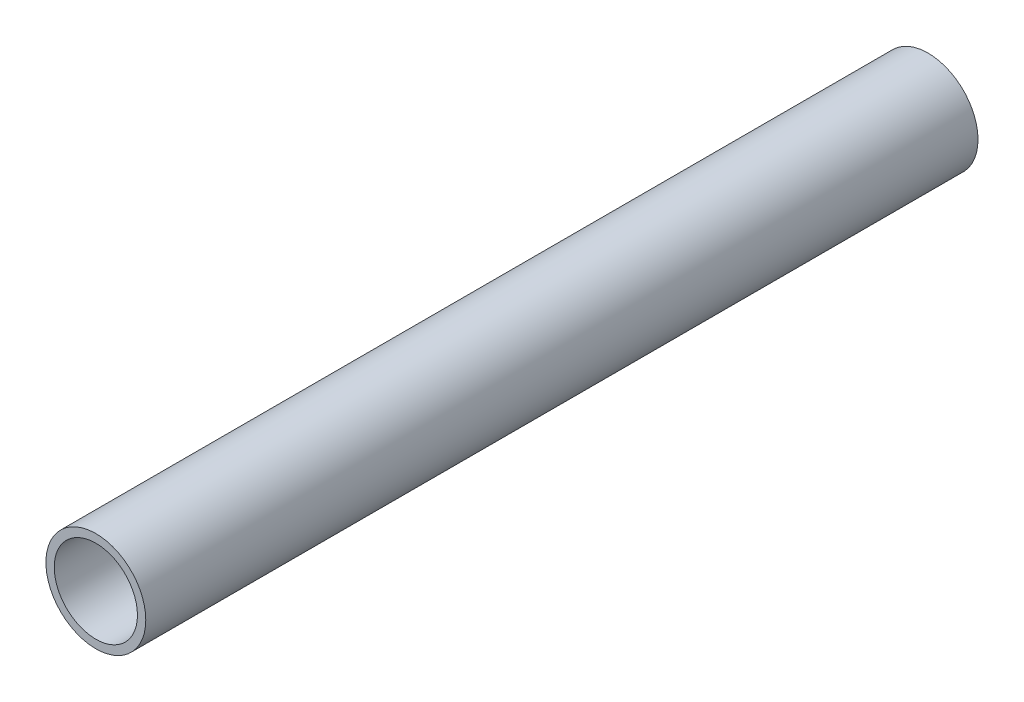
SolidWorks part; units mm, degrees
material "Thornel Mat VMA"
ref_plane "前视基准面" through (0, 0, 0) normal (0, 0, 1) x (1, 0, 0)
ref_plane "上视基准面" through (0, 0, 0) normal (0, 1, 0) x (1, 0, 0)
ref_plane "右视基准面" through (0, 0, 0) normal (1, 0, 0) x (0, 0, -1)
other "Configuration Table"
sketch "草图1" plane through (0, 0, 0) normal (0, 0, 1) x (1, 0, 0)
  circle A0 centre (0, 0) radius 5
  circle A1 centre (0, 0) radius 6
  dimension "D1" = 12
  dimension "D2" = 10
extrude "凸台-拉伸1" add sketch "草图1" along normal blind 100
